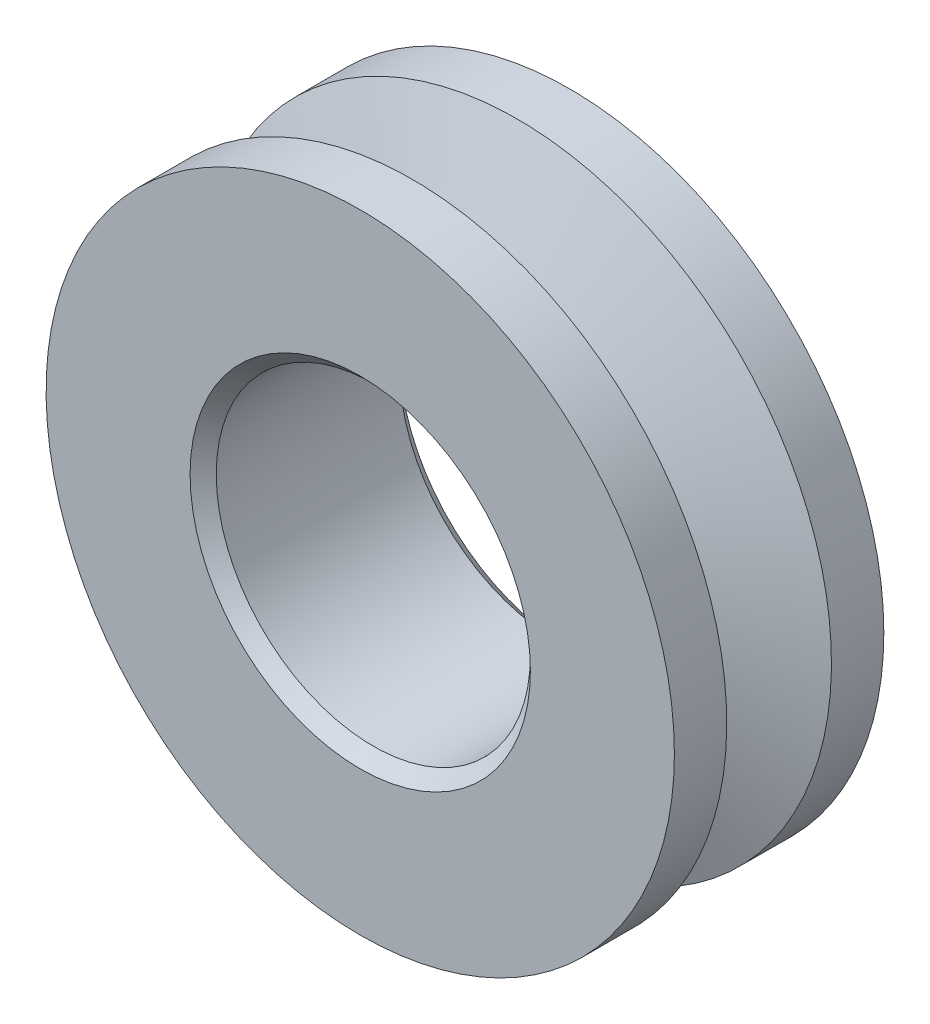
SolidWorks part; units mm, degrees
ref_plane "Front Plane" through (0, 0, 0) normal (0, 0, 1) x (1, 0, 0)
ref_plane "Top Plane" through (0, 0, 0) normal (0, 1, 0) x (1, 0, 0)
ref_plane "Right Plane" through (0, 0, 0) normal (1, 0, 0) x (0, 0, -1)
sketch "Sketch1" plane through (0, 0, 0) normal (0, 0, 1) x (1, 0, 0)
  circle A0 centre (0, 0) radius 19.05
  circle A1 centre (0, 0) radius 9.525
  dimension "D1" = 38.1
  dimension "D2" = 19.05
extrude "Extrude1" add sketch "Sketch1" along normal mid plane 12.7
sketch "Sketch2" plane through (0, 0, 0) normal (1, 0, 0) x (0, 0, -1)
  line L0 (-3.175, 19.05) -> (3.175, 19.05)
  line L2 (3.175, 19.05) -> (0.8638, 12.7)
  line L3 (0.8638, 12.7) -> (-0.8638, 12.7)
  line L4 (-0.8638, 12.7) -> (-3.175, 19.05)
  line L5 (-6.35, 0) -> (6.35, 0) construction
  line L6 (-6.35, 19.05) -> (-6.35, -19.05) construction
  line L7 (6.35, -19.05) -> (6.35, 19.05) construction
  point P2 (0, 19.05)
  point P5 (0, 12.7)
  dimension "D1" = 19.05
  dimension "D2" = 6.35
  dimension "D3" = 6.35
  dimension "D4" = 40
chamfer "Chamfer1" distance 0.7937 angle 45 2 edges at (9.525, 0, -6.35) (9.525, 0, 6.35)
revolve "Cut-Revolve1" cut sketch "Sketch2" angle 360 about L5
